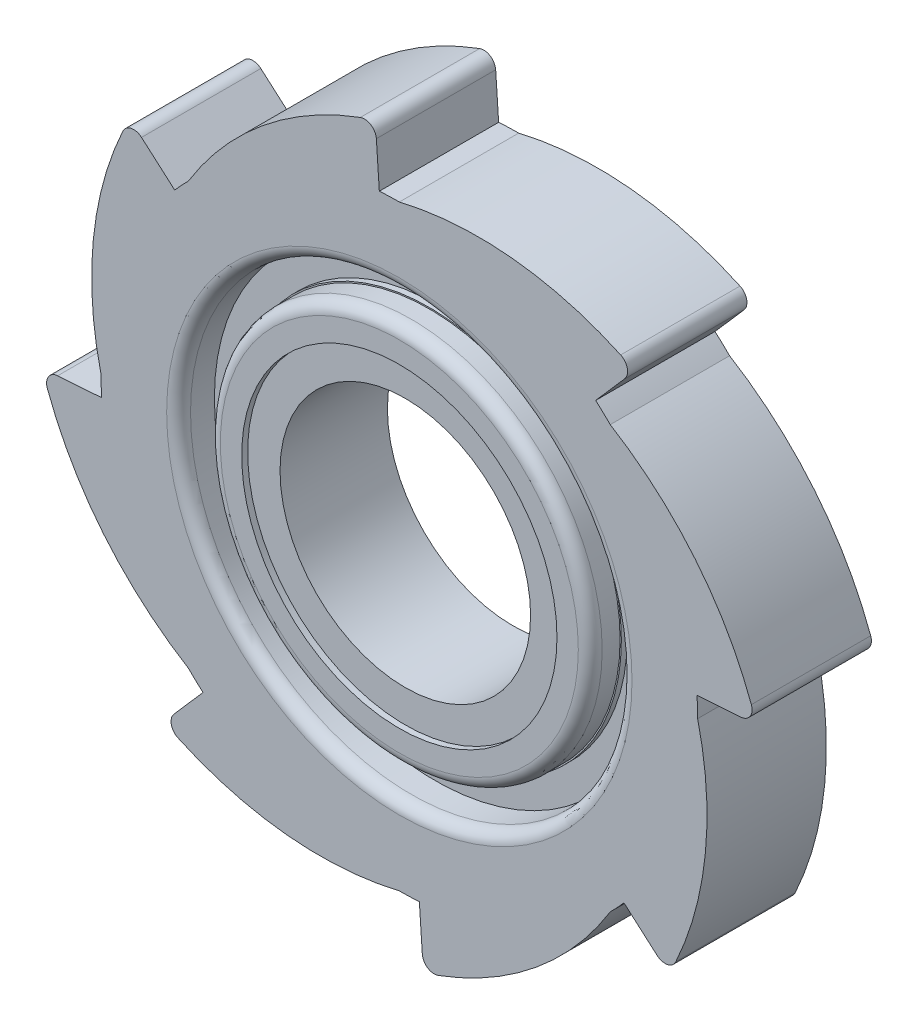
SolidWorks part; units mm, degrees
ref_plane "Front Plane" through (0, 0, 0) normal (0, 0, 1) x (1, 0, 0)
ref_plane "Top Plane" through (0, 0, 0) normal (0, 1, 0) x (1, 0, 0)
ref_plane "Right Plane" through (0, 0, 0) normal (1, 0, 0) x (0, 0, -1)
sketch "Sketch1" plane through (0, 0, 0) normal (0, 0, 1) x (1, 0, 0)
  line L0 (49.8873, 3.3556) -> (59.8647, 4.0268)
  line L1 (32.9028, 37.6484) -> (39.4834, 45.1781)
  line L2 (37.6484, -32.9028) -> (45.1781, -39.4834)
  line L3 (3.3556, -49.8873) -> (4.0268, -59.8647)
  line L4 (-32.9028, -37.6484) -> (-39.4834, -45.1781)
  line L5 (-49.8873, -3.3556) -> (-59.8647, -4.0268)
  line L6 (-37.6484, 32.9028) -> (-45.1781, 39.4834)
  line L7 (-3.3556, 49.8873) -> (-4.0268, 59.8647)
  arc A0 (0, 50) -> (-3.3556, 49.8873) centre (0, 0) ccw
  arc A1 (59.8647, 4.0268) -> (35.3553, 35.3553) centre (5.6197, -13.1594) ccw
  arc A2 (39.4834, 45.1781) -> (0, 50) centre (13.2788, -5.3314) ccw
  arc A3 (45.1781, -39.4834) -> (50, 0) centre (-5.3314, -13.2788) ccw
  arc A4 (4.0268, -59.8647) -> (35.3553, -35.3553) centre (-13.1594, -5.6197) ccw
  arc A5 (-39.4834, -45.1781) -> (0, -50) centre (-13.2788, 5.3314) ccw
  arc A6 (-59.8647, -4.0268) -> (-35.3553, -35.3553) centre (-5.6197, 13.1594) ccw
  arc A7 (-45.1781, 39.4834) -> (-50, 0) centre (5.3314, 13.2788) ccw
  arc A8 (-4.0268, 59.8647) -> (-35.3553, 35.3553) centre (13.1594, 5.6197) ccw
  arc A9 (-35.3553, 35.3553) -> (-37.6484, 32.9028) centre (0, 0) ccw
  arc A10 (-50, 0) -> (-49.8873, -3.3556) centre (0, 0) ccw
  arc A11 (-35.3553, -35.3553) -> (-32.9028, -37.6484) centre (0, 0) ccw
  arc A12 (0, -50) -> (3.3556, -49.8873) centre (0, 0) ccw
  arc A13 (35.3553, -35.3553) -> (37.6484, -32.9028) centre (0, 0) ccw
  arc A14 (50, 0) -> (49.8873, 3.3556) centre (0, 0) ccw
  arc A15 (35.3553, 35.3553) -> (32.9028, 37.6484) centre (0, 0) ccw
  circle A16 centre (0, 0) radius 21
  point P37 (0, 0)
  dimension "D1" = 8
extrude "Boss-Extrude1" add sketch "Sketch1" along normal blind 10
sketch "Sketch2" plane through (0, 0, 0) normal (0.9977, 0.0671, 0) x (0, 0, -1)
  circle A0 centre (-4.5724, 54.612) radius 1.0766
sketch "Sketch3" plane through (0, 0, 0) normal (0.9977, 0.0671, 0) x (0, 0, -1)
  circle A0 centre (-5, 56.1473) radius 1
sketch "Sketch4" plane through (0, 0, 0) normal (0.753, -0.6581, 0) x (0, 0, -1)
  circle A0 centre (-5, 55.5367) radius 1
sketch "Sketch5" plane through (0, 0, 0) normal (0.0671, -0.9977, 0) x (-0.9977, -0.0671, 0)
  circle A0 centre (-55.2588, -5) radius 1
sketch "Sketch6" plane through (0, 0, 0) normal (-0.6581, -0.753, 0) x (-0.753, 0.6581, 0)
  circle A0 centre (-55.0202, -5) radius 1
sketch "Sketch7" plane through (0, 0, 0) normal (0.6581, 0.753, 0) x (0.753, -0.6581, 0)
  circle A0 centre (-55.442, -5) radius 1
sketch "Sketch8" plane through (0, 0, 0) normal (-0.0671, 0.9977, 0) x (0.9977, 0.0671, 0)
  circle A0 centre (-55.4955, -5) radius 1
sketch "Sketch9" plane through (0, 0, 0) normal (-0.753, 0.6581, 0) x (0, 0, 1)
  circle A0 centre (5, -55.1262) radius 1
sketch "Sketch10" plane through (0, 0, 0) normal (-0.9977, -0.0671, 0) x (0, 0, 1)
  circle A0 centre (5, -55.1441) radius 1
sketch "Sketch11" plane through (0, 0, 10) normal (0, 0, 1) x (1, 0, 0)
  circle A1 centre (0, 0) radius 26.4241
extrude "Cut-Extrude2" cut sketch "Sketch11" against normal blind 1
mirror "Mirror1" of "Boss-Extrude1", "Cut-Extrude2"
fillet "Fillet1" radius 2 8 edges at (-45.1781, 39.4834, 0) (-59.8647, -4.0268, 0) (-39.4834, -45.1781, 0) (4.0268, -59.8647, 0) (45.1781, -39.4834, 0) (59.8647, 4.0268, 0) (39.4834, 45.1781, 0) (-4.0268, 59.8647, 0)
sketch "Sketch12" plane through (0, 0, 9) normal (0, 0, 1) x (1, 0, 0)
  circle A0 centre (0, 0) radius 32.217
  circle A1 centre (0, 0) radius 37
  point P169 (0, 0)
extrude "Cut-Extrude3" cut sketch "Sketch12" against normal blind 5
sketch "Sketch13" plane through (0, 0, 10) normal (0, 0, 1) x (1, 0, 0)
  circle A0 centre (0, 0) radius 32
  circle A1 centre (0, 0) radius 37
extrude "Cut-Extrude5" cut sketch "Sketch13" against normal blind 5
fillet "Fillet2" radius 2 2 edges at (32, 0, 10) (37, 0, 10)
